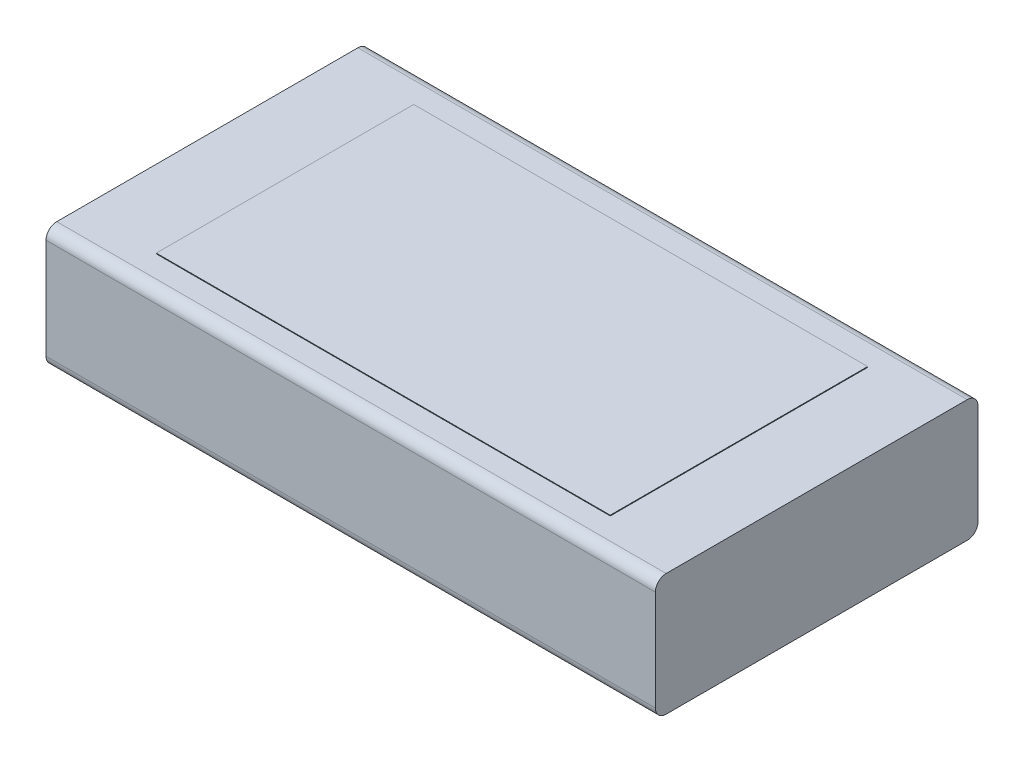
SolidWorks part; units mm, degrees
ref_plane "Plano frontal" through (0, 0, 0) normal (0, 0, 1) x (1, 0, 0)
ref_plane "Plano superior" through (0, 0, 0) normal (0, 1, 0) x (1, 0, 0)
ref_plane "Plano direito" through (0, 0, 0) normal (1, 0, 0) x (0, 0, -1)
sketch "Esboço1" plane through (0, 0, 0) normal (0, 1, 0) x (1, 0, 0)
  line L1 (-42.5, 22.5) -> (42.5, 22.5)
  line L2 (-42.5, 22.5) -> (-42.5, -22.5)
  line L3 (-42.5, -22.5) -> (42.5, -22.5)
  line L4 (42.5, 22.5) -> (42.5, -22.5)
  line L5 (-42.5, 22.5) -> (42.5, -22.5) construction
  line L6 (-42.5, -22.5) -> (42.5, 22.5) construction
  point P0 (0, 0)
  dimension "D1" = 85
  dimension "D2" = 45
extrude "Ressalto-extrusão1" add sketch "Esboço1" along normal blind 17
fillet "Filete1" radius 1.5 4 edges at (0, 0, -22.5) (0, 17, -22.5) (0, 0, 22.5) (0, 17, 22.5)
sketch "Esboço2" plane through (0, 17, 0) normal (0, 1, 0) x (1, 0, 0)
  line L1 (31.6578, -17.9523) -> (-31.6578, -17.9523)
  line L2 (31.6578, -17.9523) -> (31.6578, 17.9523)
  line L3 (31.6578, 17.9523) -> (-31.6578, 17.9523)
  line L4 (-31.6578, -17.9523) -> (-31.6578, 17.9523)
  line L5 (31.6578, -17.9523) -> (-31.6578, 17.9523) construction
  line L6 (31.6578, 17.9523) -> (-31.6578, -17.9523) construction
  point P0 (0, 0)
extrude "Ressalto-extrusão2" add sketch "Esboço2" along normal blind 0.1
